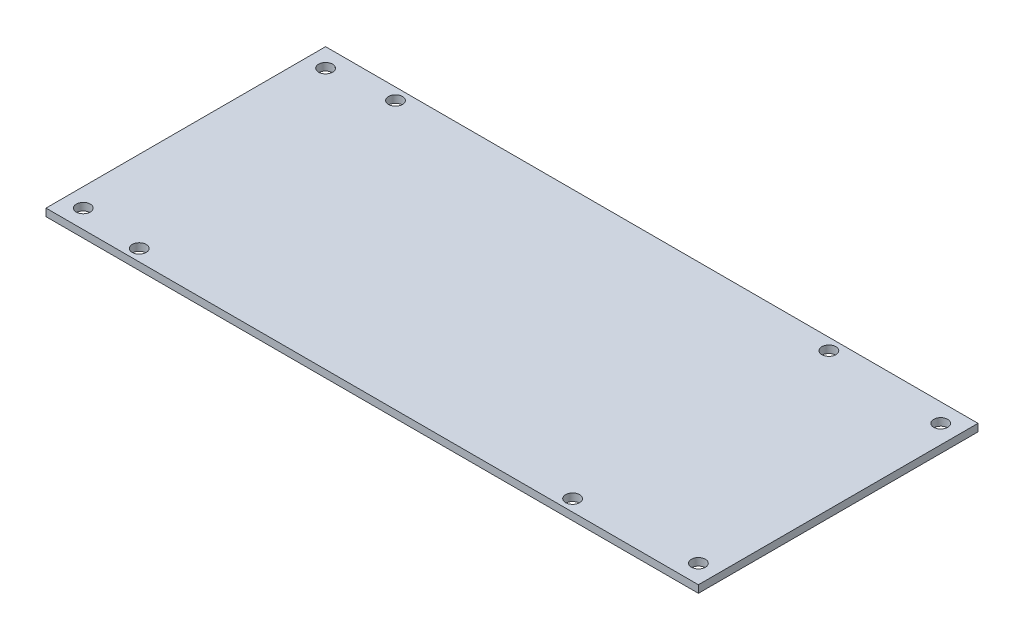
SolidWorks part; units mm, degrees
ref_plane "Спереди" through (0, 0, 0) normal (0, 0, 1) x (1, 0, 0)
ref_plane "Сверху" through (0, 0, 0) normal (0, 1, 0) x (1, 0, 0)
ref_plane "Справа" through (0, 0, 0) normal (1, 0, 0) x (0, 0, -1)
sketch "Эскиз1" plane through (0, 0, 0) normal (0, 1, 0) x (1, 0, 0)
  line L1 (-70, 30) -> (70, 30)
  line L2 (-70, 30) -> (-70, -30)
  line L3 (-70, -30) -> (70, -30)
  line L4 (70, 30) -> (70, -30)
  line L5 (-70, 30) -> (70, -30) construction
  line L6 (-70, -30) -> (70, 30) construction
  point P0 (0, 0)
  dimension "D1" = 140
  dimension "D2" = 60
extrude "Бобышка-Вытянуть1" add sketch "Эскиз1" along normal blind 1.6
sketch "Эскиз2" plane through (0, 1.6, 0) normal (0, 1, 0) x (1, 0, 0)
  line L0 (0, 30) -> (0, -30) construction
  line L1 (70, 30) -> (-70, 30) construction
  line L2 (-70, -30) -> (70, -30) construction
  line L3 (-70, 0) -> (70, 0) construction
  line L4 (-70, 30) -> (-70, -30) construction
  line L5 (70, -30) -> (70, 30) construction
  line L6 (-66, 30) -> (-66, -30) construction
  line L7 (-70, 26) -> (70, 26) construction
  circle A0 centre (-66, 26) radius 1.5
  circle A1 centre (-66, -26) radius 1.5
  circle A2 centre (66, -26) radius 1.5
  circle A3 centre (66, 26) radius 1.5
  point P18 (0, 0)
  dimension "D3" = 3
  dimension "D1" = 4
  dimension "D2" = 4
extrude "Вырез-Вытянуть1" cut sketch "Эскиз2" against normal up to surface (1.6 mm away) up to face at (0, 0, 0)
sketch "Эскиз3" plane through (0, 1.6, 0) normal (0, 1, 0) x (1, 0, 0)
  line L0 (-70, 27.5) -> (70, 27.5) construction
  line L1 (-70, 30) -> (-70, -30) construction
  line L2 (70, -30) -> (70, 30) construction
  line L3 (0, 30) -> (0, -30) construction
  line L4 (70, 30) -> (-70, 30) construction
  line L5 (-70, -30) -> (70, -30) construction
  line L6 (-70, 0) -> (70, 0) construction
  line L7 (-52.5, 30) -> (-52.5, -30) construction
  line L8 (40.5, 30) -> (40.5, -30) construction
  circle A0 centre (-52.5, 27.5) radius 1.5
  circle A1 centre (-52.5, -27.5) radius 1.5
  circle A2 centre (40.5, 27.5) radius 1.5
  circle A3 centre (40.5, -27.5) radius 1.5
  dimension "D3" = 3
  dimension "D1" = 2.5
  dimension "D2" = 17.5
  dimension "D4" = 93
extrude "Вырез-Вытянуть2" cut sketch "Эскиз3" against normal up to surface (1.6 mm away) up to face at (-66, 0, 27.5)
